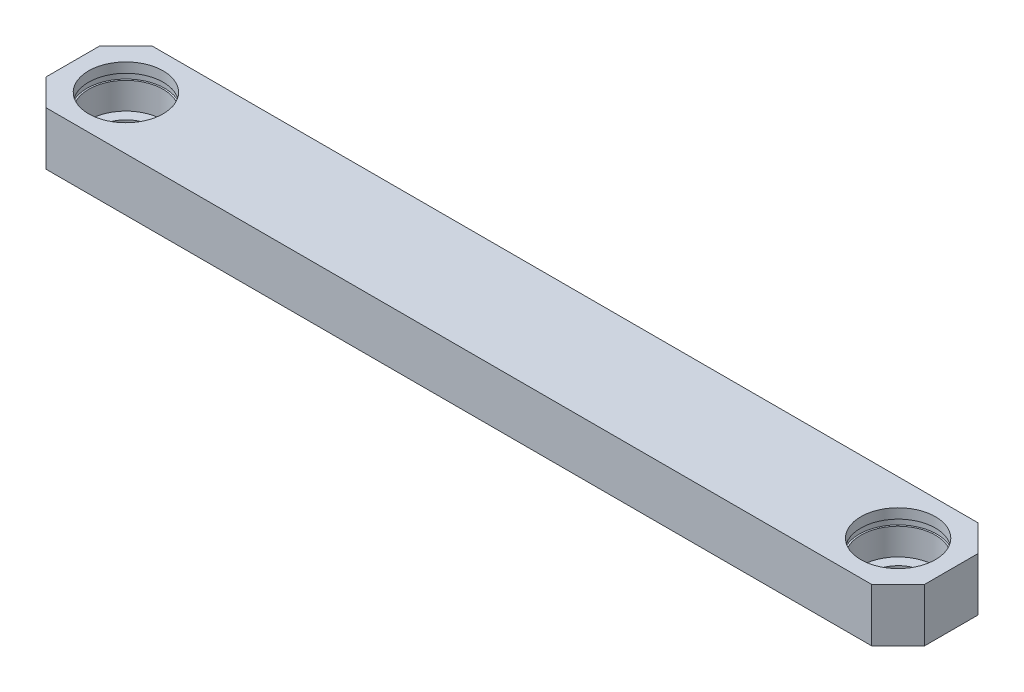
SolidWorks part; units mm, degrees
ref_plane "Front Plane" through (0, 0, 0) normal (0, 0, 1) x (1, 0, 0)
ref_plane "Top Plane" through (0, 0, 0) normal (0, 1, 0) x (1, 0, 0)
ref_plane "Right Plane" through (0, 0, 0) normal (1, 0, 0) x (0, 0, -1)
sketch "Sketch1" plane through (0, 0, 0) normal (0, 1, 0) x (1, 0, 0)
  line L0 (10, 10) -> (10, -10) construction
  line L1 (0, 10) -> (165, 10)
  line L2 (0, 10) -> (0, -10)
  line L3 (0, -10) -> (165, -10)
  line L4 (165, 10) -> (165, -10)
  line L5 (155, 10) -> (155, -10) construction
  dimension "L_s" = 165
  dimension "W" = 20
  dimension "F" = 10
  dimension "L" = 145
  dimension "MSM_11" = 10
extrude "Boss-Extrude1" add sketch "Sketch1" along normal blind 10
chamfer "Chamfer1" distance 5 angle 45 4 edges at (0, 5, -10) (165, 5, -10) (165, 5, 10) (0, 5, 10)
sketch "Sketch2" plane through (0, 0, 0) normal (0, 0, 1) x (1, 0, 0)
  line L0 (2.7, 7) -> (3, 7)
  line L1 (3, 7) -> (3, 2)
  line L2 (2.7, 8.15) -> (2.7, 7)
  line L3 (3, 2) -> (5, 2)
  line L4 (5, 2) -> (5, 0)
  line L5 (7.5, 10) -> (7.5, 0) construction
  line L6 (12.5, 10) -> (12.5, 0) construction
  line L7 (5, 0) -> (160, 0) construction
  line L8 (10, 10) -> (10, 0)
  line L9 (10, 0) -> (5, 0)
  line L10 (5, 10) -> (160, 10) construction
  line L11 (10, 10) -> (3, 10)
  line L12 (0, 10) -> (5, 10) construction
  line L13 (3, 10) -> (3, 8.15)
  line L14 (3, 8.15) -> (2.7, 8.15)
  line L15 (10, 10) -> (10, 0) construction
  line L16 (7.5, 10) -> (12.5, 10) construction
  line L17 (12.5, 0) -> (7.5, 0) construction
  dimension "D1" = 2
  dimension "D1._1" = 14
  dimension "DH_s_1" = 10
  dimension "MSM_1" = 14.6
  dimension "F" = 10
  dimension "B_1" = 5
  dimension "MSM_2" = 1.15
  dimension "D1_s" = 5
revolve "Cut-Revolve1" cut sketch "Sketch2" angle 360 about L15
hole_wizard "Diameter Hole1" [suppressed] positions "Sketch4" profile "Sketch3" hole size "Ø3.0" standard "JIS"
sketch "Sketch4" [suppressed] plane through (0, 10, 0) normal (0, 1, 0) x (1, 0, 0)
  line L0 (10, 10) -> (10, -10) construction
  line L1 (37, 10) -> (5, 10) construction
  line L2 (5, -10) -> (37, -10) construction
  point P0 (30, 0)
  dimension "L" = 145
  dimension "F" = 10
sketch "Sketch3" [suppressed] plane through (30, 10, 0) normal (1, 0, 0) x (0, 0, 1)
  line L0 (0, 0) -> (0, 10)
  line L1 (0, 10) -> (1.5, 10)
  line L2 (1.5, 10) -> (1.5, 0)
  line L5 (1.5, 0) -> (0, 0)
  line L11 (0, 0) -> (0, 10) construction
  dimension "E" = 3
  dimension "Thru Hole Depth" = 10
hole_wizard "Tapped Hole1" [suppressed] positions "Sketch6" profile "Sketch5" tap size "M3x0.5" standard "JIS"
sketch "Sketch6" [suppressed] plane through (0, 0, -10) normal (0, 0, -1) x (-1, 0, 0)
  line L0 (-10, 10) -> (-10, 0) construction
  line L1 (-37, 10) -> (-5, 10) construction
  line L2 (-37, 0) -> (-5, 0) construction
  point P0 (-30, 5)
  dimension "F" = 10
  dimension "L" = 145
  dimension "D1" = 5
sketch "Sketch5" [suppressed] plane through (30, 5, -10) normal (1, 0, 0) x (0, 1, 0)
  line L0 (0, 0) -> (0, 20)
  line L1 (0, 20) -> (1.25, 20)
  line L2 (1.25, 20) -> (1.25, 0)
  line L5 (1.25, 0) -> (0, 0)
  line L11 (0, 0) -> (0, 20) construction
  dimension "Thru Tap Drill Dia." = 2.5
  dimension "Thru Tap Drill Depth" = 20
cosmetic thread "Hole Thread1" [suppressed] parameters "M"=3
sketch "Sketch7" plane through (0, 0, 0) normal (0, 0, 1) x (1, 0, 0)
  line L0 (157.5, 0) -> (157.5, 10) construction
  line L1 (10, 10) -> (10, 0) construction
  line L2 (5, 10) -> (160, 10) construction
  line L3 (5, 0) -> (160, 0) construction
  line L4 (155, 10) -> (155, 0) construction
  line L5 (152.5, 10) -> (152.5, 0) construction
  line L6 (152.5, 0) -> (157.5, 0) construction
  line L7 (152.5, 10) -> (157.5, 10) construction
  line L8 (148, 10) -> (148, 8.15)
  line L9 (148, 8.15) -> (147.7, 8.15)
  line L10 (147.7, 8.15) -> (147.7, 7)
  line L11 (147.7, 7) -> (148, 7)
  line L12 (148, 7) -> (148, 2)
  line L13 (148, 2) -> (150, 2)
  line L14 (150, 2) -> (150, 0)
  line L15 (150, 0) -> (155, 0)
  line L16 (155, 10) -> (155, 0)
  line L17 (148, 10) -> (155, 10)
  dimension "D1" = 2
  dimension "F" = 10
  dimension "L" = 145
  dimension "D1._2" = 14
  dimension "MSM_6" = 14.6
  dimension "MSM_7" = 1.15
  dimension "B_2" = 5
  dimension "DH_s_2" = 10
  dimension "D2_s" = 5
revolve "Cut-Revolve2" cut sketch "Sketch7" angle 360 about L4
equation "\"D1@Sketch6\" = \"T@Boss-Extrude1\" / 2"
